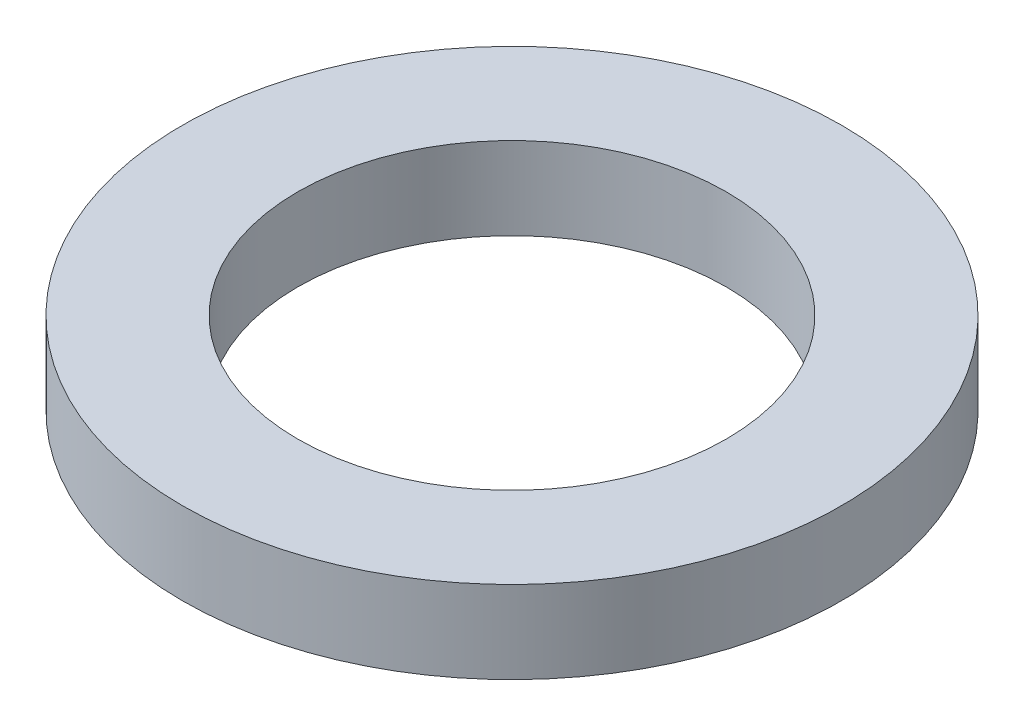
SolidWorks part; units mm, degrees
ref_plane "Front Plane" through (0, 0, 0) normal (0, 0, 1) x (1, 0, 0)
ref_plane "Top Plane" through (0, 0, 0) normal (0, 1, 0) x (1, 0, 0)
ref_plane "Right Plane" through (0, 0, 0) normal (1, 0, 0) x (0, 0, -1)
sketch "Sketch1" plane through (0, 0, 0) normal (0, 1, 0) x (1, 0, 0)
  circle A0 centre (0, 0) radius 13
  circle A1 centre (0, 0) radius 20
extrude "Boss-Extrude1" add sketch "Sketch1" along normal blind 5
